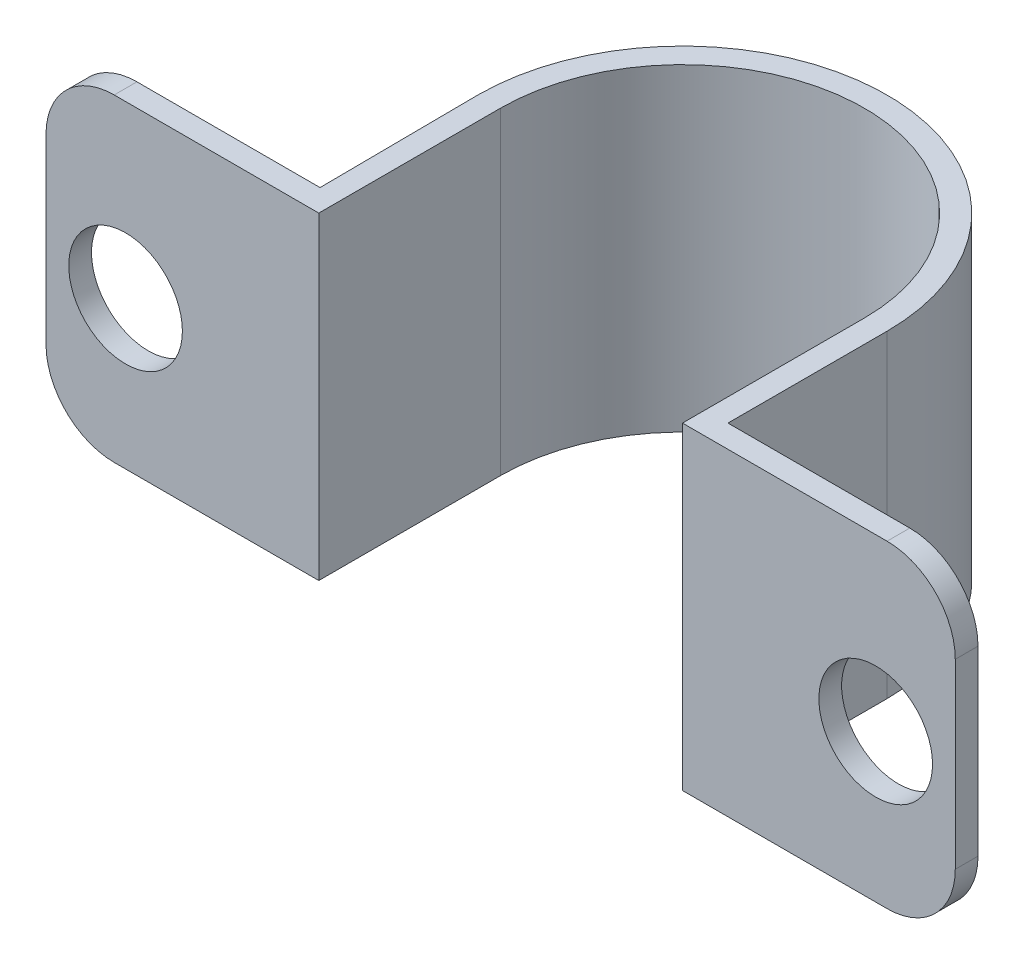
SolidWorks part; units mm, degrees
ref_plane "Alzado" through (0, 0, 0) normal (0, 0, 1) x (1, 0, 0)
ref_plane "Planta" through (0, 0, 0) normal (0, 1, 0) x (1, 0, 0)
ref_plane "Vista lateral" through (0, 0, 0) normal (1, 0, 0) x (0, 0, -1)
sketch "Croquis1" plane through (0, 0, 0) normal (0, 1, 0) x (1, 0, 0)
  line L0 (-8, 0) -> (-20, 0)
  line L1 (-55, 0) -> (55, 0) construction
  line L2 (-20, 0) -> (-20, 1)
  line L3 (-8, 8) -> (-8, 0)
  line L4 (-8, 0) -> (-20, 0)
  line L5 (8, 0) -> (20, 0)
  line L6 (20, 0) -> (20, 1)
  line L7 (20, 1) -> (8.9443, 1)
  line L8 (-20, 1) -> (-8.9443, 1)
  line L9 (-9, 8) -> (-8.9443, 1)
  line L10 (9, 8) -> (9, 1)
  line L11 (8, 0) -> (8, 8)
  arc A3 (9, 8) -> (-8.9989, 7.8567) centre (0, 8) ccw
  arc A4 (8, 8) -> (-8, 8) centre (0, 8) ccw
extrude "Saliente-Extruir1" add sketch "Croquis1" along normal blind 14
fillet "Redondeo1" radius 3 4 edges at (20, 0, -0.5) (20, 14, -0.5) (-20, 14, -0.5) (-20, 0, -0.5)
sketch "Croquis2" plane through (0, 0, 0) normal (0, 0, 1) x (1, 0, 0)
  line L0 (-8, 14) -> (-17, 14) construction
  line L2 (0, -7.7) -> (0, 7.7) construction
  circle A0 centre (-16.5, 6.5) radius 2.5
  circle A1 centre (16.5, 6.5) radius 2.5
  point P6 (12.0578, 6.5)
  point P7 (12.0578, 6.5)
  dimension "D5" = 5
  dimension "D6" = 5
  dimension "D1" = 7.5
  dimension "D2" = 0
  dimension "D3" = 33
  dimension "D4" = 16.5
extrude "Cortar-Extruir1" cut sketch "Croquis2" against normal blind 10
